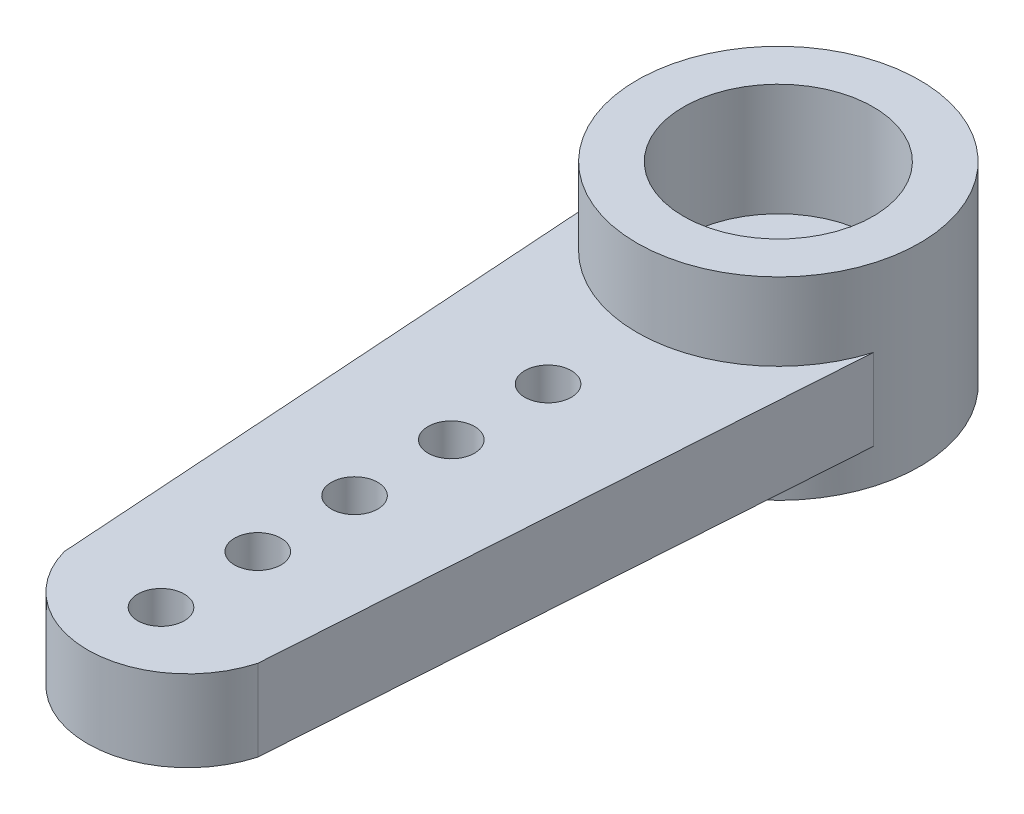
SolidWorks part; units mm, degrees
other "标注1"
sketch "草图8" plane through (-3.65, 2.5, 17.85) normal (-0.1568, 0.9864, 0.0498) x (0.1299, -0.0294, 0.9911)
ref_plane "前视基准面" through (0, 0, 0) normal (0, 0, 1) x (1, 0, 0)
ref_plane "上视基准面" through (0, 0, 0) normal (0, 1, 0) x (1, 0, 0)
ref_plane "右视基准面" through (0, 0, 0) normal (1, 0, 0) x (0, 0, -1)
sketch "草图3" plane through (0, 0, 0) normal (0, 1, 0) x (1, 0, 0)
  circle A0 centre (0, 0) radius 3.65
  dimension "D1" = 7.3
extrude "凸台-拉伸1" add sketch "草图3" along normal mid plane 5
sketch "草图4" plane through (0, 2.5, 0) normal (0, 1, 0) x (1, 0, 0)
  circle A0 centre (0, 0) radius 2.45
  dimension "D1" = 4.9
extrude "切除-拉伸1" cut sketch "草图4" against normal blind 2.9
sketch "草图5" plane through (0, -0.4, 0) normal (0, 1, 0) x (1, 0, 0)
  circle A0 centre (0, 0) radius 1.3
  dimension "D1" = 2.6
extrude "切除-拉伸2" cut sketch "草图5" against normal through all
ref_plane "基准面1" through (0, 0.5, 0) normal (0, 1, 0) x (1, 0, 0)
sketch "草图6" plane through (0, 0.5, 0) normal (0, 1, 0) x (1, 0, 0)
  line L0 (0, 0) -> (4.051, 0) construction
  line L1 (0, 0) -> (0, -50000) construction
  line L2 (3.5, -1.0356) -> (-3.5, -1.0356) construction
  line L3 (2.5, -15.95) -> (-2.5, -15.95) construction
  line L4 (3.5, -1.0356) -> (2.5, -15.95)
  line L5 (-3.5, -1.0356) -> (-2.5, -15.95)
  circle A0 centre (0, 0) radius 3.65 construction
  arc A1 (2.5, -15.95) -> (-2.5, -15.95) centre (0, -15.2553) cw
  arc A2 (3.5, -1.0356) -> (-3.5, -1.0356) centre (0, 0) cw
  point P2 (2.7579, -2.6496)
  point P10 (0, 3.65)
  point P11 (0, -17.85)
  point P14 (0, -15.95)
  dimension "D1" = 7
  dimension "D2" = 21.5
  dimension "D3" = 5
  dimension "D4" = 1.9
extrude "凸台-拉伸2" add sketch "草图6" against normal blind 2.1
sketch "草图7" plane through (0, 0.5, 0) normal (0, 1, 0) x (1, 0, 0)
  line L0 (0, -15.95) -> (0, -13.45) construction
  arc A0 (-2.5, -15.95) -> (2.5, -15.95) centre (0, -15.2553) ccw construction
  circle A1 centre (0, -15.95) radius 0.6
  circle A2 centre (0, -13.45) radius 0.6
  circle A3 centre (0, -10.95) radius 0.6
  circle A4 centre (0, -8.45) radius 0.6
  circle A5 centre (0, -5.95) radius 0.6
  point P0 (0, -15.95)
  point P4 (0, -17.85)
  point P9 (0, -13.45)
  point P12 (0, -10.95)
  point P15 (0, -8.45)
  point P18 (0, -5.95)
  dimension "D2" = 1.2
  dimension "D1" = 1.9
  dimension "D4" = 2.5
  dimension "D3" = 5
extrude "切除-拉伸3" cut sketch "草图7" against normal blind 10
